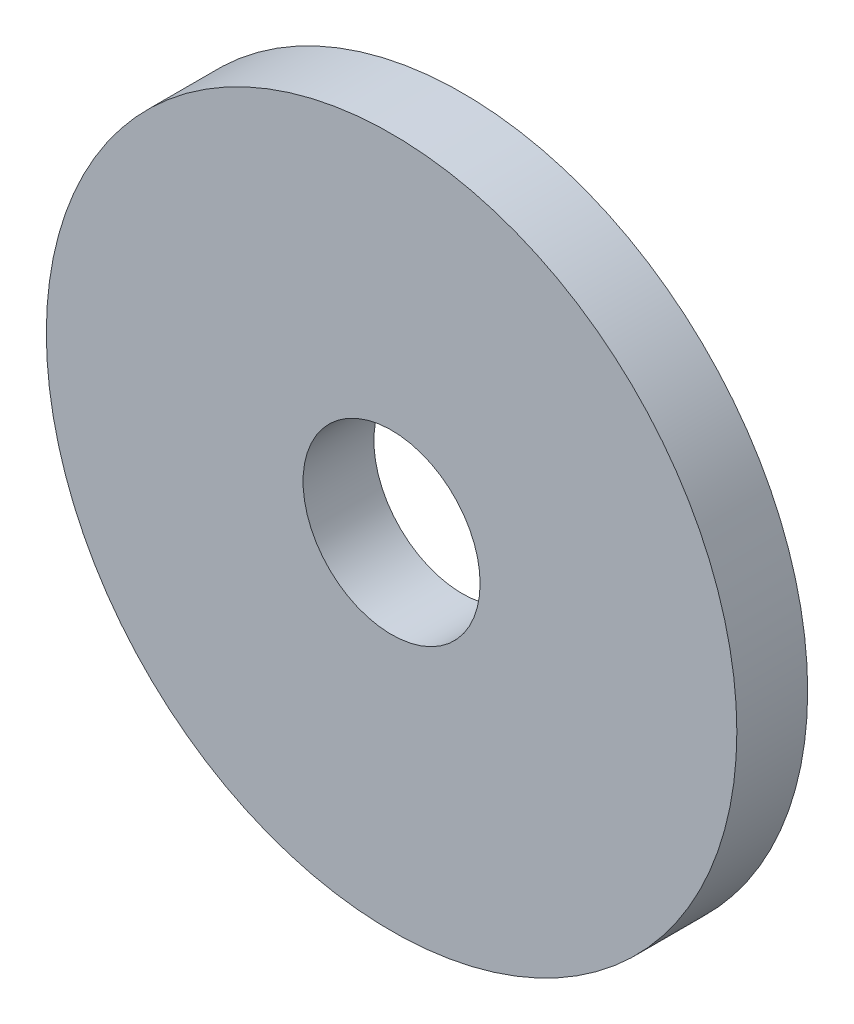
SolidWorks part; units mm, degrees
ref_plane "前视基准面" through (0, 0, 0) normal (0, 0, 1) x (1, 0, 0)
ref_plane "上视基准面" through (0, 0, 0) normal (0, 1, 0) x (1, 0, 0)
ref_plane "右视基准面" through (0, 0, 0) normal (1, 0, 0) x (0, 0, -1)
sketch "草图1" plane through (0, 0, 0) normal (0, 0, 1) x (1, 0, 0)
  circle A0 centre (0, 0) radius 1.5
  circle A1 centre (0, 0) radius 5.85
  dimension "D1" = 3
  dimension "D2" = 11.7
extrude "凸台-拉伸1" add sketch "草图1" along normal blind 1.2
